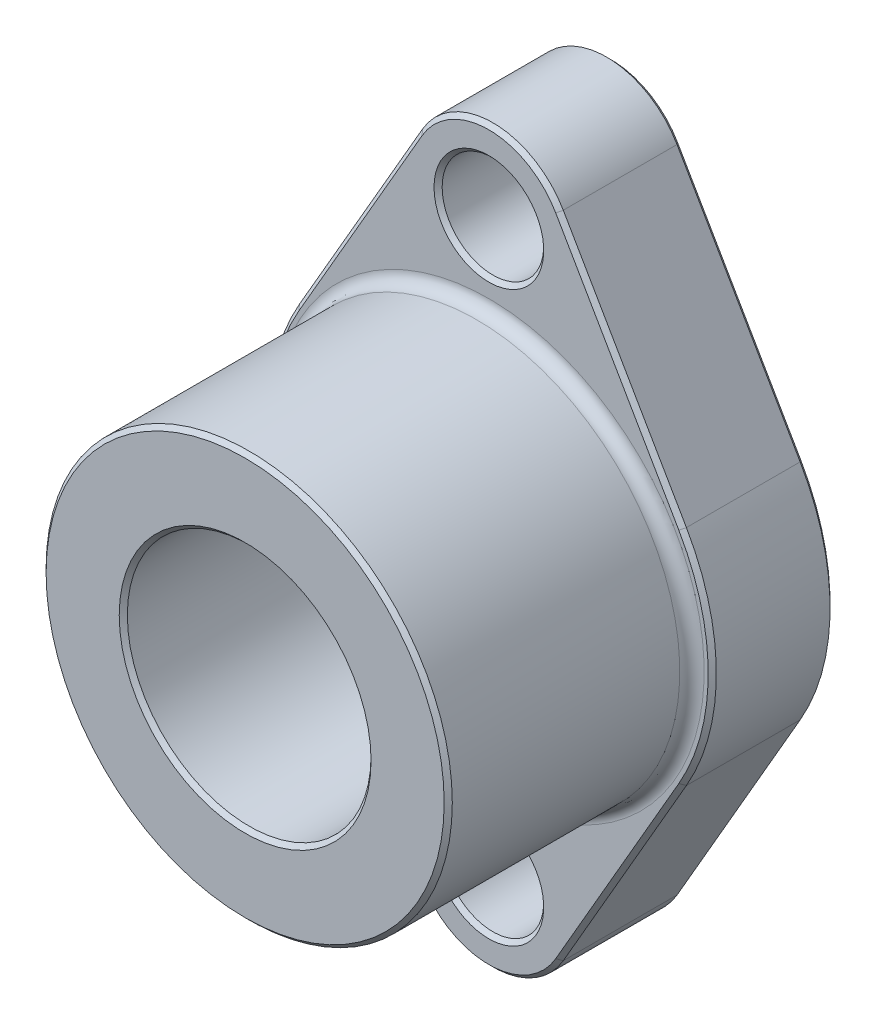
SolidWorks part; units mm, degrees
ref_plane "Front Plane" through (0, 0, 0) normal (0, 0, 1) x (1, 0, 0)
ref_plane "Top Plane" through (0, 0, 0) normal (0, 1, 0) x (1, 0, 0)
ref_plane "Right Plane" through (0, 0, 0) normal (1, 0, 0) x (0, 0, -1)
sketch "Sketch1" plane through (0, 0, 0) normal (0, 0, 1) x (1, 0, 0)
  circle A0 centre (0, 0) radius 5
  dimension "D1" = 10
extrude "Boss-Extrude1" add sketch "Sketch1" along normal blind 6
sketch "Sketch2" plane through (0, 0, 0) normal (0, 0, -1) x (-1, 0, 0)
  line L0 (-4.7631, 2.75) -> (-1.7321, 8)
  line L1 (0, 7) -> (0, 0) construction
  line L2 (0, 0) -> (-12.5719, 0) construction
  line L3 (-4.7631, -2.75) -> (-1.7321, -8)
  line L4 (4.7631, -2.75) -> (1.7321, -8)
  line L5 (4.7631, 2.75) -> (1.7321, 8)
  arc A0 (-4.7631, 2.75) -> (-4.7631, -2.75) centre (0, 0) ccw
  arc A1 (1.7321, 8) -> (-1.7321, 8) centre (0, 7) ccw
  arc A2 (-1.7321, -8) -> (1.7321, -8) centre (0, -7) ccw
  arc A3 (4.7631, -2.75) -> (4.7631, 2.75) centre (0, 0) ccw
  point P1 (-27.7842, -0.4176)
  dimension "D1" = 11
  dimension "D2" = 4
  dimension "D5" = 4
  dimension "D3" = 7
  dimension "D4" = 7
extrude "Boss-Extrude2" add sketch "Sketch2" along normal blind 3
sketch "Sketch3" plane through (0, 0, -3) normal (0, 0, -1) x (-1, 0, 0)
  circle A0 centre (0, 0) radius 3
  circle A1 centre (0, 7) radius 1.25
  circle A2 centre (0, -7) radius 1.25
  point P7 (0, 0)
  point P8 (0, 0)
  dimension "D1" = 6
  dimension "D2" = 2.5
  dimension "D3" = 2.5
  dimension "D4" = 7
  dimension "D5" = 7
extrude "Cut-Extrude1" cut sketch "Sketch3" against normal through all
fillet "Fillet1" radius 0.3 1 edges at (5, 0, 0)
chamfer "Chamfer1" distance 0.1 angle 45 23 edges at (3.2476, 5.375, -3) (0, 9, -3) (-3.2476, 5.375, -3) (-5.5, 0, -3) (-3.2476, -5.375, -3) (0, -9, -3) (3.2476, -5.375, -3) (5.5, 0, -3) (-1.25, 7, -3) (-1.25, -7, -3) (3.2476, -5.375, 0) (0, -9, 0) (-3.2476, -5.375, 0) (-5.5, 0, 0) (-3.2476, 5.375, 0) (0, 9, 0) (3.2476, 5.375, 0) (5.5, 0, 0) (-1.25, 7, 0) (-1.25, -7, 0) (5, 0, 6) (-3, 0, -3) (-3, 0, 6)
